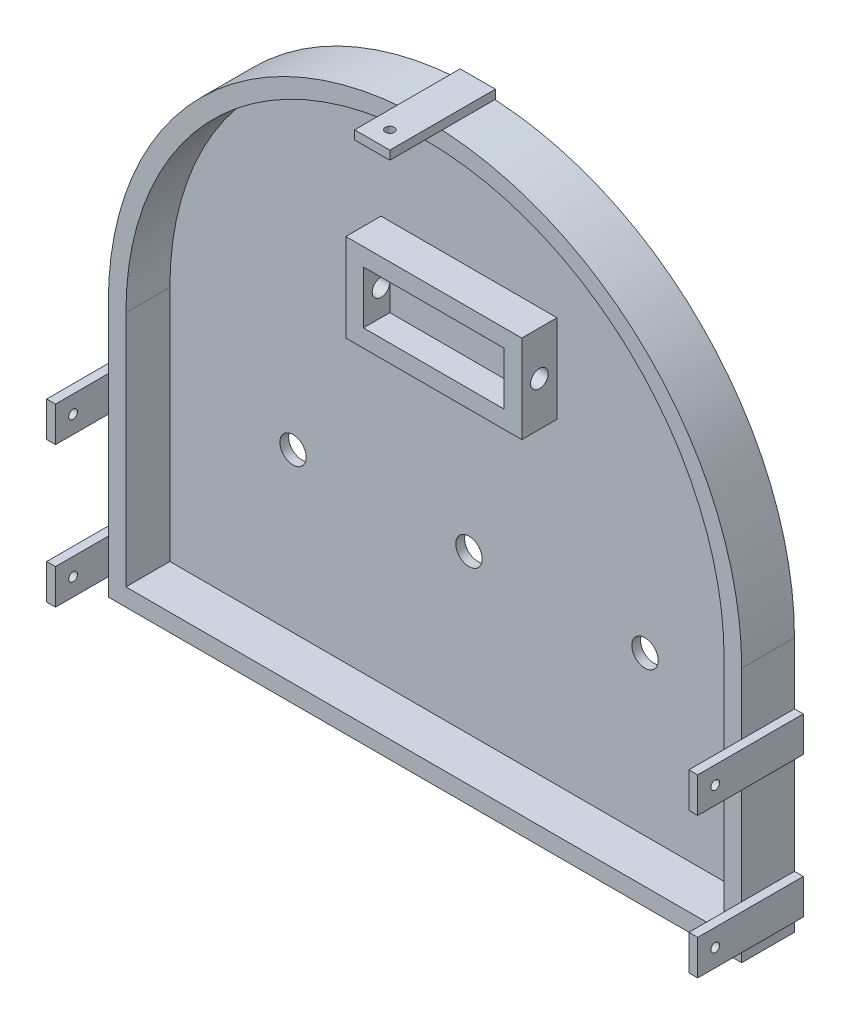
SolidWorks part; units mm, degrees
material "Ceramic Porcelain"
ref_plane "Front Plane" through (0, 0, 0) normal (0, 0, 1) x (1, 0, 0)
ref_plane "Top Plane" through (0, 0, 0) normal (0, 1, 0) x (1, 0, 0)
ref_plane "Right Plane" through (0, 0, 0) normal (1, 0, 0) x (0, 0, -1)
sketch "Sketch1" plane through (0, 0, 0) normal (0, 0, 1) x (1, 0, 0)
  line L0 (-180, 0) -> (-180, -145)
  line L1 (-180, -145) -> (180, -145)
  line L2 (180, -145) -> (180, 0)
  arc A0 (180, 0) -> (-180, 0) centre (0, 0) ccw
  dimension "D1" = 360
  dimension "D2" = 145
extrude "Boss-Extrude1" add sketch "Sketch1" along normal blind 5
sketch "Sketch3" plane through (0, 0, 0) normal (0, 0, 1) x (1, 0, 0)
  line L0 (-180, -145) -> (180, -145) construction
  line L2 (-170, 0) -> (-170, -135)
  line L3 (-170, -135) -> (170, -135)
  line L4 (170, 0) -> (170, -135)
  line L5 (-180, 0) -> (-180, -145) construction
  line L6 (180, -145) -> (180, 0) construction
  line L7 (-180, 0) -> (-180, -145)
  line L8 (-180, -145) -> (180, -145)
  line L9 (180, -145) -> (180, 0)
  arc A5 (170, 0) -> (-170, 0) centre (0, 0) ccw
  arc A6 (180, 0) -> (-180, 0) centre (0, 0) ccw construction
  arc A7 (180, 0) -> (-180, 0) centre (0, 0) ccw
  dimension "D1" = 10
  dimension "D2" = 10
  dimension "D3" = 135
  dimension "D4" = 10
extrude "Boss-Extrude2" add sketch "Sketch3" along normal blind 30
sketch "Sketch4" plane through (0, 0, 5) normal (0, 0, 1) x (1, 0, 0)
  line L0 (0, 170) -> (0, -145.5929) construction
  line L1 (-121.8417, 135) -> (120.3975, 135) construction
  line L2 (-180, -145) -> (180, -145) construction
  line L4 (-50, 95) -> (50, 95)
  line L5 (-50, 95) -> (-50, 45)
  line L6 (-50, 45) -> (50, 45)
  line L7 (50, 95) -> (50, 45)
  arc A0 (170, 0) -> (-170, 0) centre (0, 0) ccw construction
  point P15 (0, 95)
  dimension "D1" = 280
  dimension "D2" = 40
  dimension "D3" = 100
  dimension "D4" = 50
extrude "Boss-Extrude3" add sketch "Sketch4" along normal blind 20
shell "Shell1" thickness 10
sketch "Sketch5" plane through (50, 0, 0) normal (1, 0, 0) x (0, 0, -1)
  line L3 (-25, 95) -> (-5, 95) construction
  line L4 (-25, 45) -> (-25, 95) construction
  circle A0 centre (-15, 70) radius 5
  point P6 (-36.6478, 80.4572)
  dimension "D1" = 10
  dimension "D2" = 25
  dimension "D3" = 10
extrude "Cut-Extrude1" cut sketch "Sketch5" against normal blind 20
mirror "Mirror1" about plane through (0, 0, 0) normal (1, 0, 0) of "Cut-Extrude1"
sketch "Sketch6" plane through (180, 0, 0) normal (1, 0, 0) x (0, 0, -1)
  line L0 (0, -145) -> (0, 0) construction
  line L1 (0, -135) -> (-60, -135)
  line L2 (0, -135) -> (0, -115)
  line L3 (0, -115) -> (-60, -115)
  line L4 (-60, -135) -> (-60, -115)
  line L5 (-52.8975, -85) -> (52.6816, -85) construction
  line L6 (-60, -125) -> (0, -125) construction
  line L7 (-16.7682, -125) -> (-16.7682, -145) construction
  line L8 (-30, -145) -> (0, -145) construction
  line L9 (-30, -145) -> (-30, 0) construction
  line L10 (0, -55) -> (-60, -55)
  line L11 (-60, -35) -> (-60, -55)
  line L12 (0, -35) -> (-60, -35)
  line L13 (0, -35) -> (0, -55)
  circle A0 centre (-50, -125) radius 2.5
  circle A1 centre (-50, -45) radius 2.5
  dimension "D4" = 5
  dimension "D1" = 60
  dimension "D2" = 20
  dimension "D3" = 20
  dimension "D5" = 20
  dimension "D6" = 16.7682
  dimension "D7" = 40
extrude "Boss-Extrude4" add sketch "Sketch6" along normal blind 5
mirror "Mirror2" about plane through (0, 0, 0) normal (1, 0, 0) of "Boss-Extrude4"
ref_plane "Plane1" through (0, 180, 0) normal (0, 1, 0) x (1, 0, 0)
sketch "Sketch8" plane through (0, 180, 0) normal (0, 1, 0) x (1, 0, 0)
  line L0 (180, 0) -> (-180, 0) construction
  line L1 (-10, 0) -> (10, 0)
  line L2 (-10, 0) -> (-10, -60)
  line L3 (-10, -60) -> (10, -60)
  line L4 (10, 0) -> (10, -60)
  line L5 (0, 0) -> (0, -60) construction
  line L6 (-180, -30) -> (180, -30) construction
  circle A0 centre (0, -50) radius 2.5
  point P6 (0, 0)
  dimension "D3" = 5
  dimension "D1" = 60
  dimension "D2" = 20
  dimension "D4" = 20
extrude "Boss-Extrude5" add sketch "Sketch8" along normal blind 5 separate body
sketch "Sketch9" plane through (0, 0, 0) normal (0, 0, -1) x (-1, 0, 0)
  line L0 (180, -145) -> (-180, -145) construction
  circle A0 centre (-100, -45) radius 7.5
  circle A1 centre (0, -45) radius 7.5
  circle A2 centre (100, -45) radius 7.5
  point P9 (0, 0)
  dimension "D1" = 15
  dimension "D2" = 100
  dimension "D3" = 100
  dimension "D4" = 100
extrude "Cut-Extrude2" cut sketch "Sketch9" against normal through all both and the other way through all
